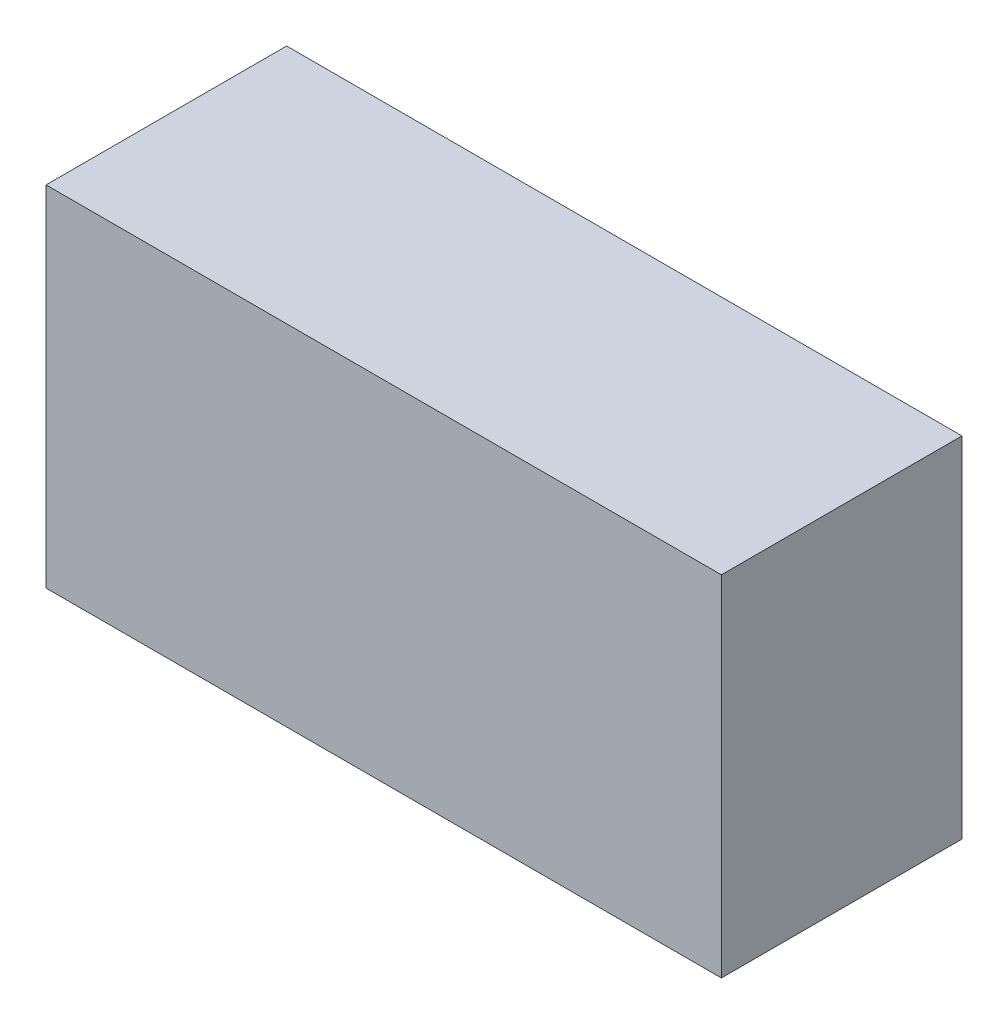
SolidWorks part; units mm, degrees
ref_plane "Front Plane" through (0, 0, 0) normal (0, 0, 1) x (1, 0, 0)
ref_plane "Top Plane" through (0, 0, 0) normal (0, 1, 0) x (1, 0, 0)
ref_plane "Right Plane" through (0, 0, 0) normal (1, 0, 0) x (0, 0, -1)
sketch "Sketch1" plane through (0, 0, 0) normal (0, 1, 0) x (1, 0, 0)
  line L1 (-9.825, 3.5) -> (9.825, 3.5)
  line L2 (-9.825, 3.5) -> (-9.825, -3.5)
  line L3 (-9.825, -3.5) -> (9.825, -3.5)
  line L4 (9.825, 3.5) -> (9.825, -3.5)
  line L5 (-9.825, 3.5) -> (9.825, -3.5) construction
  line L6 (-9.825, -3.5) -> (9.825, 3.5) construction
  point P0 (0, 0)
  dimension "D1" = 7
  dimension "D2" = 19.65
extrude "Boss-Extrude1" add sketch "Sketch1" along normal blind 10.16
sketch "Sketch2" plane through (0, 0, 0) normal (0, -1, 0) x (1, 0, 0)
  line L0 (0, -3.5) -> (0, -2.8) construction
  line L1 (9.825, -3.5) -> (-9.825, -3.5) construction
  line L2 (0, -2.8) -> (0.005, -2.8) construction
  line L3 (0.005, -2.8) -> (2.545, -2.8) construction
  line L4 (2.545, -2.8) -> (5.085, -2.8) construction
  line L5 (0.005, -2.8) -> (-5.075, -2.8) construction
  line L6 (-5.075, -2.8) -> (-7.615, -2.8) construction
  line L7 (-9.825, -3.5) -> (-9.825, 3.5) construction
  circle A0 centre (0.005, -2.8) radius 0.25
  circle A1 centre (2.545, -2.8) radius 0.25
  circle A2 centre (5.085, -2.8) radius 0.25
  circle A3 centre (-5.075, -2.8) radius 0.25
  circle A4 centre (-7.615, -2.8) radius 0.25
  dimension "D2" = 0.005
  dimension "D3" = 0.5
  dimension "D1" = 0.7
  dimension "D4" = 2.21
  dimension "D5" = 2.54
  dimension "D6" = 2.54
  dimension "D7" = 2.54
extrude "Boss-Extrude2" add sketch "Sketch2" along normal blind 4.1
